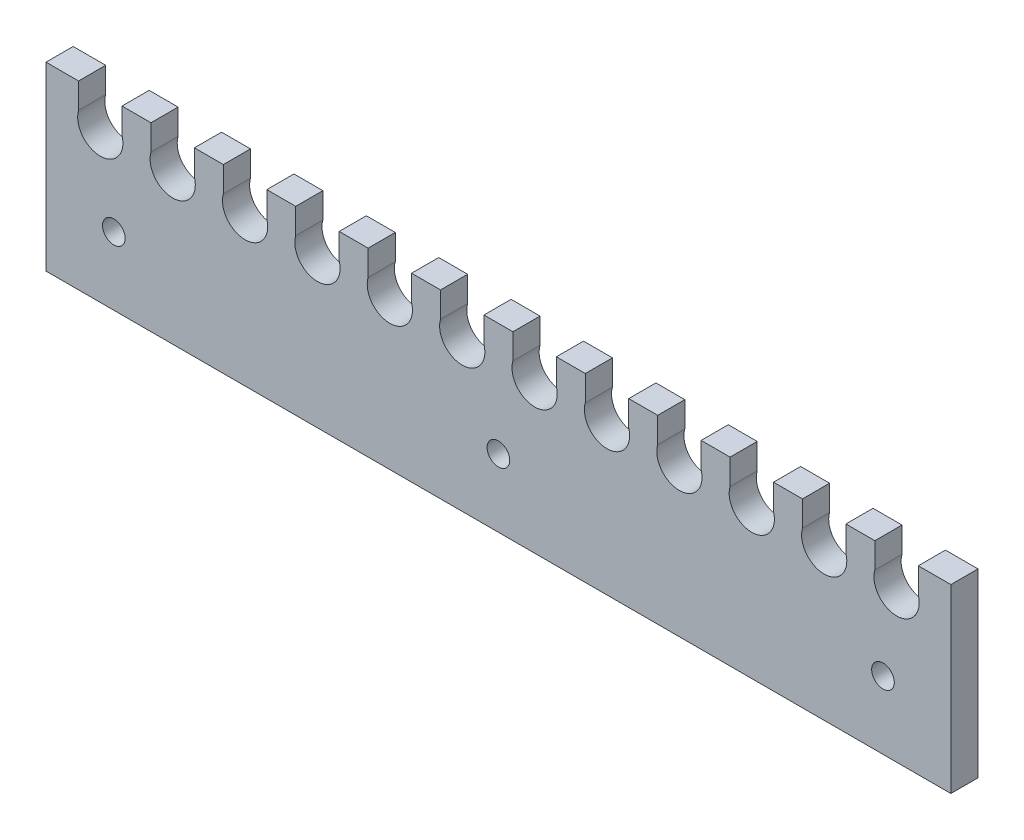
SolidWorks part; units mm, degrees
material "Sapin"
ref_plane "Plan de face" through (0, 0, 0) normal (0, 0, 1) x (1, 0, 0)
ref_plane "Plan de dessus" through (0, 0, 0) normal (0, 1, 0) x (1, 0, 0)
ref_plane "Plan de droite" through (0, 0, 0) normal (1, 0, 0) x (0, 0, -1)
sketch "Esquisse1" plane through (0, 0, 0) normal (0, 0, 1) x (1, 0, 0)
  line L1 (-100, -20) -> (100, -20)
  line L2 (-100, -20) -> (-100, 20)
  line L3 (-100, 20) -> (100, 20)
  line L4 (100, -20) -> (100, 20)
  line L5 (-100, -20) -> (100, 20) construction
  line L6 (-100, 20) -> (100, -20) construction
  point P0 (0, 0)
  dimension "D1" = 200
  dimension "D2" = 40
extrude "Boss.-Extru.1" add sketch "Esquisse1" along normal blind 6
sketch "Esquisse2" plane through (0, 0, 6) normal (0, 0, 1) x (1, 0, 0)
  line L0 (-92.8, 14.4) -> (-92.8, 20)
  line L1 (100, 20) -> (-100, 20) construction
  line L2 (-92.8, 20) -> (-83.2, 20)
  line L3 (-83.2, 20) -> (-83.2, 14.4)
  line L4 (-100, 20) -> (-100, -20) construction
  arc A0 (-92.8, 14.4) -> (-83.2, 14.4) centre (-88, 13) ccw
  dimension "D2" = 5
  dimension "D1" = 9.6
  dimension "D3" = 7
  dimension "D4" = 12
extrude "Enlèv. mat.-Extru.1" cut sketch "Esquisse2" against normal through all
sketch "Esquisse3" plane through (0, 0, 6) normal (0, 0, 1) x (1, 0, 0)
  line L0 (-85, -5) -> (85, -5) construction
  line L5 (-100, -20) -> (100, -20) construction
  line L6 (-100, 20) -> (-100, -20) construction
  circle A0 centre (-85, -5) radius 2.5
  circle A1 centre (85, -5) radius 2.5
  circle A2 centre (0, -5) radius 2.5
  point P4 (0, -5)
  dimension "D2" = 5
  dimension "D1" = 15
  dimension "D3" = 15
extrude "Enlèv. mat.-Extru.2" cut sketch "Esquisse3" against normal through all
pattern_linear "Répétition linéaire1" count 12 spacing 16 along (1, 0, 0) of "Enlèv. mat.-Extru.1"
